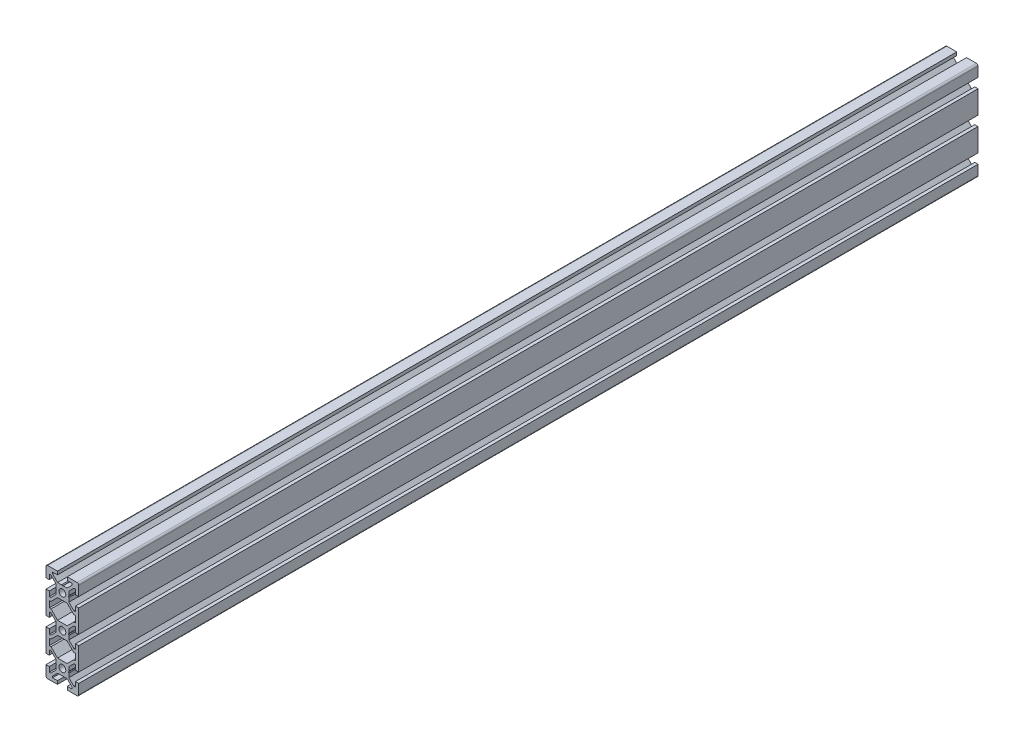
SolidWorks part; units mm, degrees
material "6061 Alloy"
ref_plane "Front Plane" through (0, 0, 0) normal (0, 0, 1) x (1, 0, 0)
ref_plane "Top Plane" through (0, 0, 0) normal (0, 1, 0) x (1, 0, 0)
ref_plane "Right Plane" through (0, 0, 0) normal (1, 0, 0) x (0, 0, -1)
ref_plane "Plane1" through (0, 0, 0) normal (0, 0, 1) x (1, 0, 0)
sketch "Sketch1" plane through (0, 0, 0) normal (0, 0, 1) x (1, 0, 0)
  line L0 (-10, -17) -> (-8, -17)
  line L1 (-8, -17) -> (-8, -14)
  line L2 (-8, -14) -> (-7.0607, -14)
  line L3 (-7.0607, -14) -> (-4, -17.0607)
  line L4 (-4, -17.0607) -> (-4, -19.4804)
  line L5 (-4, -19.4804) -> (-3.7, -20)
  line L6 (-3.7, -20) -> (-4, -20.5196)
  line L7 (-4, -20.5196) -> (-4, -22.9393)
  line L8 (-4, -22.9393) -> (-7.0607, -26)
  line L9 (-7.0607, -26) -> (-8, -26)
  line L10 (-8, -26) -> (-8, -23)
  line L11 (-8, -23) -> (-10, -23)
  line L12 (-10, -23) -> (-10, -29)
  line L13 (-9, -30) -> (-3, -30)
  line L14 (-3, -30) -> (-3, -28)
  line L15 (-3, -28) -> (-6, -28)
  line L16 (-6, -28) -> (-6, -27.0607)
  line L17 (-6, -27.0607) -> (-2.9393, -24)
  line L18 (-2.9393, -24) -> (-0.5196, -24)
  line L19 (-0.5196, -24) -> (0, -23.7)
  line L20 (0, -23.7) -> (0.5196, -24)
  line L21 (0.5196, -24) -> (2.9393, -24)
  line L22 (2.9393, -24) -> (6, -27.0607)
  line L23 (6, -27.0607) -> (6, -28)
  line L24 (6, -28) -> (3, -28)
  line L25 (3, -28) -> (3, -30)
  line L26 (3, -30) -> (9, -30)
  line L27 (10, -29) -> (10, -23)
  line L28 (10, -23) -> (8, -23)
  line L29 (8, -23) -> (8, -26)
  line L30 (8, -26) -> (7.0607, -26)
  line L31 (7.0607, -26) -> (4, -22.9393)
  line L32 (4, -22.9393) -> (4, -20.5196)
  line L33 (4, -20.5196) -> (3.7, -20)
  line L34 (3.7, -20) -> (4, -19.4804)
  line L35 (4, -19.4804) -> (4, -17.0607)
  line L36 (4, -17.0607) -> (7.0607, -14)
  line L37 (7.0607, -14) -> (8, -14)
  line L38 (8, -14) -> (8, -17)
  line L39 (8, -17) -> (10, -17)
  line L40 (10, -17) -> (10, -3)
  line L41 (10, -3) -> (8, -3)
  line L42 (8, -3) -> (8, -6)
  line L43 (8, -6) -> (7.0607, -6)
  line L44 (7.0607, -6) -> (4, -2.9393)
  line L45 (4, -2.9393) -> (4, -0.5196)
  line L46 (4, -0.5196) -> (3.7, 0)
  line L47 (3.7, 0) -> (4, 0.5196)
  line L48 (4, 0.5196) -> (4, 2.9393)
  line L49 (4, 2.9393) -> (7.0607, 6)
  line L50 (7.0607, 6) -> (8, 6)
  line L51 (8, 6) -> (8, 3)
  line L52 (8, 3) -> (10, 3)
  line L53 (10, 3) -> (10, 17)
  line L54 (10, 17) -> (8, 17)
  line L55 (8, 17) -> (8, 14)
  line L56 (8, 14) -> (7.0607, 14)
  line L57 (7.0607, 14) -> (4, 17.0607)
  line L58 (4, 17.0607) -> (4, 19.4804)
  line L59 (4, 19.4804) -> (3.7, 20)
  line L60 (3.7, 20) -> (4, 20.5196)
  line L61 (4, 20.5196) -> (4, 22.9393)
  line L62 (4, 22.9393) -> (7.0607, 26)
  line L63 (7.0607, 26) -> (8, 26)
  line L64 (8, 26) -> (8, 23)
  line L65 (8, 23) -> (10, 23)
  line L66 (10, 23) -> (10, 29)
  line L67 (9, 30) -> (3, 30)
  line L68 (3, 30) -> (3, 28)
  line L69 (3, 28) -> (6, 28)
  line L70 (6, 28) -> (6, 27.0607)
  line L71 (6, 27.0607) -> (2.9393, 24)
  line L72 (2.9393, 24) -> (0.5196, 24)
  line L73 (0.5196, 24) -> (0, 23.7)
  line L74 (0, 23.7) -> (-0.5196, 24)
  line L75 (-0.5196, 24) -> (-2.9393, 24)
  line L76 (-2.9393, 24) -> (-6, 27.0607)
  line L77 (-6, 27.0607) -> (-6, 28)
  line L78 (-6, 28) -> (-3, 28)
  line L79 (-3, 28) -> (-3, 30)
  line L80 (-3, 30) -> (-9, 30)
  line L81 (-10, 29) -> (-10, 23)
  line L82 (-10, 23) -> (-8, 23)
  line L83 (-8, 23) -> (-8, 26)
  line L84 (-8, 26) -> (-7.0607, 26)
  line L85 (-7.0607, 26) -> (-4, 22.9393)
  line L86 (-4, 22.9393) -> (-4, 20.5196)
  line L87 (-4, 20.5196) -> (-3.7, 20)
  line L88 (-3.7, 20) -> (-4, 19.4804)
  line L89 (-4, 19.4804) -> (-4, 17.0607)
  line L90 (-4, 17.0607) -> (-7.0607, 14)
  line L91 (-7.0607, 14) -> (-8, 14)
  line L92 (-8, 14) -> (-8, 17)
  line L93 (-8, 17) -> (-10, 17)
  line L94 (-10, 17) -> (-10, 3)
  line L95 (-10, 3) -> (-8, 3)
  line L96 (-8, 3) -> (-8, 6)
  line L97 (-8, 6) -> (-7.0607, 6)
  line L98 (-7.0607, 6) -> (-4, 2.9393)
  line L99 (-4, 2.9393) -> (-4, 0.5196)
  line L100 (-4, 0.5196) -> (-3.7, 0)
  line L101 (-3.7, 0) -> (-4, -0.5196)
  line L102 (-4, -0.5196) -> (-4, -2.9393)
  line L103 (-4, -2.9393) -> (-7.0607, -6)
  line L104 (-7.0607, -6) -> (-8, -6)
  line L105 (-8, -6) -> (-8, -3)
  line L106 (-8, -3) -> (-10, -3)
  line L107 (-10, -3) -> (-10, -17)
  line L108 (-8, 8) -> (-6.9393, 8)
  line L109 (-6.9393, 8) -> (-2.9393, 4)
  line L110 (-2.9393, 4) -> (2.9393, 4)
  line L111 (2.9393, 4) -> (6.9393, 8)
  line L112 (6.9393, 8) -> (8, 8)
  line L113 (8, 8) -> (8, 12)
  line L114 (8, 12) -> (6.9393, 12)
  line L115 (6.9393, 12) -> (2.9393, 16)
  line L116 (2.9393, 16) -> (-2.9393, 16)
  line L117 (-2.9393, 16) -> (-6.9393, 12)
  line L118 (-6.9393, 12) -> (-8, 12)
  line L119 (-8, 12) -> (-8, 8)
  line L120 (-8, -8) -> (-8, -12)
  line L121 (-8, -12) -> (-6.9393, -12)
  line L122 (-6.9393, -12) -> (-2.9393, -16)
  line L123 (-2.9393, -16) -> (2.9393, -16)
  line L124 (2.9393, -16) -> (6.9393, -12)
  line L125 (6.9393, -12) -> (8, -12)
  line L126 (8, -12) -> (8, -8)
  line L127 (8, -8) -> (6.9393, -8)
  line L128 (6.9393, -8) -> (2.9393, -4)
  line L129 (2.9393, -4) -> (-2.9393, -4)
  line L130 (-2.9393, -4) -> (-6.9393, -8)
  line L131 (-6.9393, -8) -> (-8, -8)
  arc A0 (-10, -29) -> (-9, -30) centre (-9, -29) ccw
  arc A1 (9, -30) -> (10, -29) centre (9, -29) ccw
  arc A2 (10, 29) -> (9, 30) centre (9, 29) ccw
  arc A3 (-9, 30) -> (-10, 29) centre (-9, 29) ccw
extrude "Boss-Extrude1" add sketch "Sketch1" against normal blind 550
ref_plane "Plane2" through (0, 0, 0) normal (1, 0, 0) x (0, 0, -1)
sketch "Sketch2" plane through (0, 0, 0) normal (1, 0, 0) x (0, 0, -1)
  line L0 (550, 20) -> (550, 17.9)
  line L1 (550, 17.9) -> (0, 17.9)
  line L2 (0, 17.9) -> (0, 20)
  line L3 (0, 20) -> (550, 20)
  line L4 (0, 20) -> (550, 20) construction
revolve "Cut-Revolve1" cut sketch "Sketch2" angle 360 about L4
ref_plane "Plane3" through (0, 0, 0) normal (1, 0, 0) x (0, 0, -1)
sketch "Sketch3" plane through (0, 0, 0) normal (1, 0, 0) x (0, 0, -1)
  line L0 (550, 0) -> (550, -2.1)
  line L1 (550, -2.1) -> (0, -2.1)
  line L2 (0, -2.1) -> (0, 0)
  line L3 (0, 0) -> (550, 0)
  line L4 (0, 0) -> (550, 0) construction
revolve "Cut-Revolve2" cut sketch "Sketch3" angle 360 about L4
ref_plane "Plane4" through (0, 0, 0) normal (1, 0, 0) x (0, 0, -1)
sketch "Sketch4" plane through (0, 0, 0) normal (1, 0, 0) x (0, 0, -1)
  line L0 (550, -20) -> (550, -22.1)
  line L1 (550, -22.1) -> (0, -22.1)
  line L2 (0, -22.1) -> (0, -20)
  line L3 (0, -20) -> (550, -20)
  line L4 (0, -20) -> (550, -20) construction
revolve "Cut-Revolve3" cut sketch "Sketch4" angle 360 about L4
